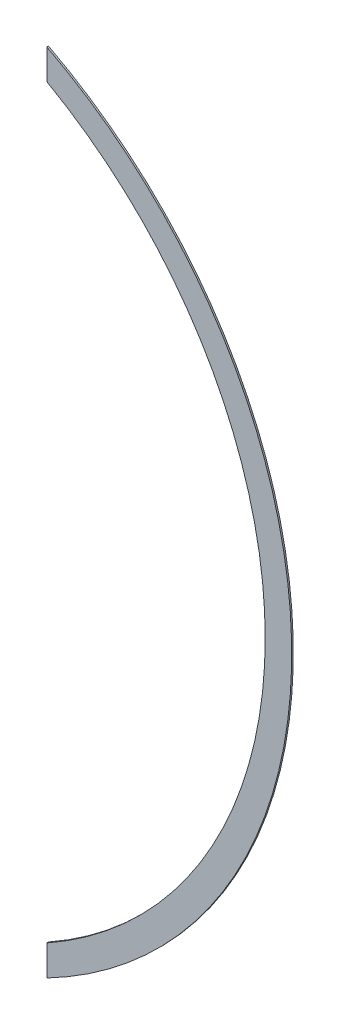
SolidWorks part; units mm, degrees
material "Galvanized Steel"
ref_plane "Front Plane" through (0, 0, 0) normal (0, 0, 1) x (1, 0, 0)
ref_plane "Top Plane" through (0, 0, 0) normal (0, 1, 0) x (1, 0, 0)
ref_plane "Right Plane" through (0, 0, 0) normal (1, 0, 0) x (0, 0, -1)
sketch "Sketch1" plane through (0, 0, 0) normal (0, 0, 1) x (1, 0, 0)
  line L0 (-107.4522, -370.2812) -> (-107.4522, -341.8721)
  line L1 (-107.4522, 355.8376) -> (-107.4522, 384.0176)
  arc A0 (-107.4522, -370.2812) -> (-107.4522, 384.0176) centre (-303.3689, 6.8682) ccw
  arc A1 (-107.4522, -341.8721) -> (-107.4522, 355.8376) centre (-303.1568, 6.9828) ccw
  dimension "D1" = 400
  dimension "D2" = 425
extrude "Boss-Extrude1" add sketch "Sketch1" along normal blind 1.5
